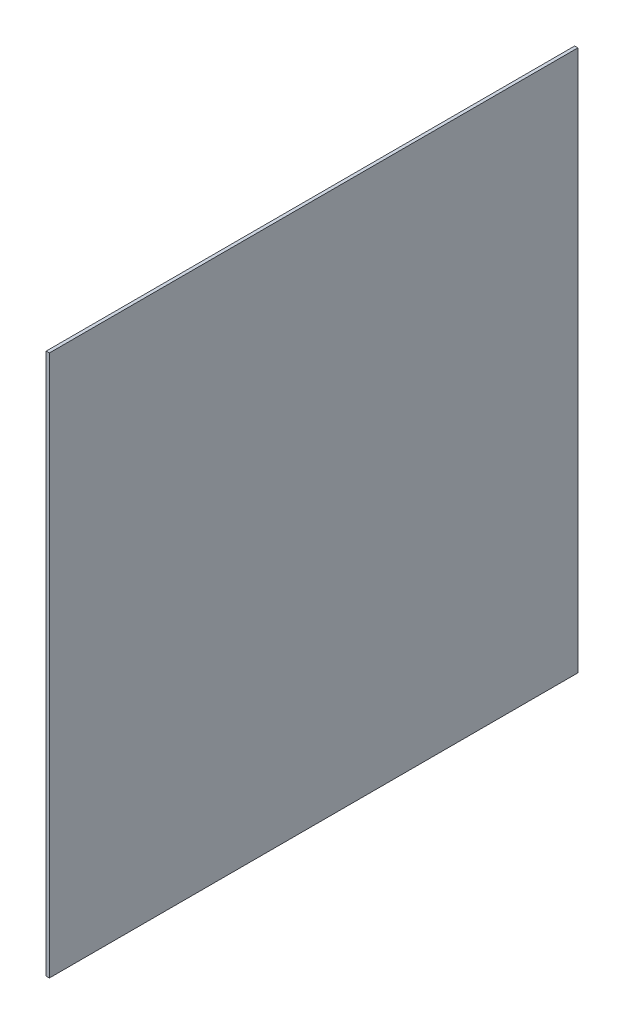
SolidWorks part; units mm, degrees
ref_plane "Front Plane" through (0, 0, 0) normal (0, 0, 1) x (1, 0, 0)
ref_plane "Top Plane" through (0, 0, 0) normal (0, 1, 0) x (1, 0, 0)
ref_plane "Right Plane" through (0, 0, 0) normal (1, 0, 0) x (0, 0, -1)
sketch "Sketch1" plane through (0, 0, 0) normal (1, 0, 0) x (0, 0, -1)
  line L1 (0, 0) -> (2082.8, 0)
  line L2 (0, 0) -> (0, 2133.6)
  line L3 (0, 2133.6) -> (2082.8, 2133.6)
  line L4 (2082.8, 0) -> (2082.8, 2133.6)
  dimension "D1" = 2082.8
  dimension "D2" = 2133.6
extrude "Boss-Extrude1" add sketch "Sketch1" along normal blind 12.7
